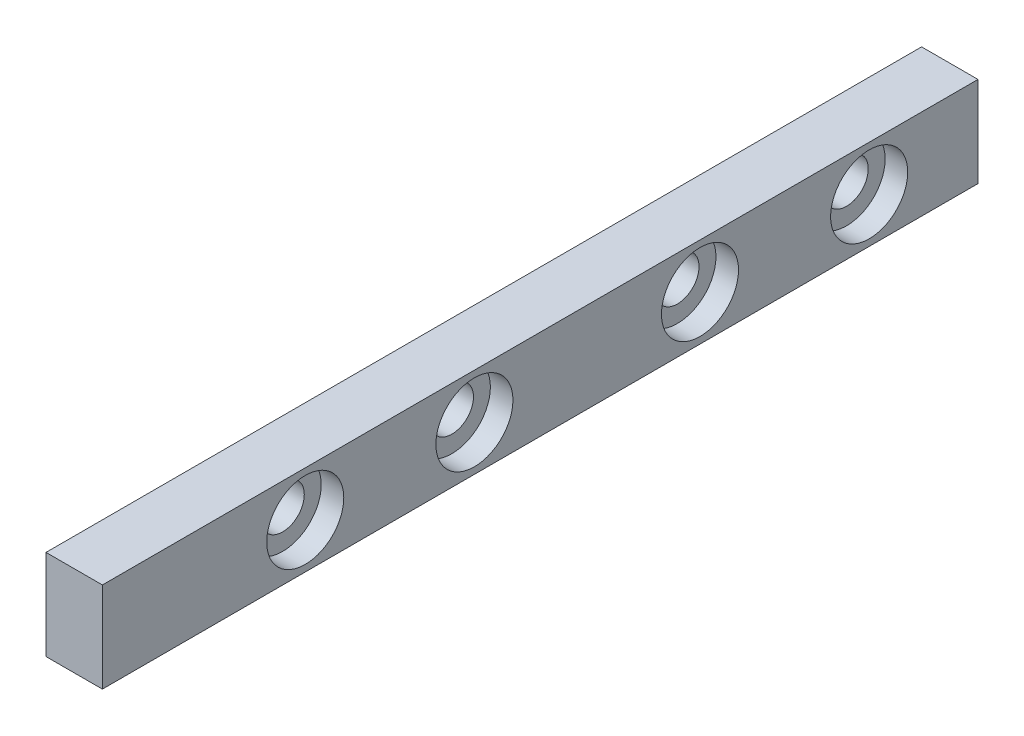
SolidWorks part; units mm, degrees
ref_plane "前视基准面" through (0, 0, 0) normal (0, 0, 1) x (1, 0, 0)
ref_plane "上视基准面" through (0, 0, 0) normal (0, 1, 0) x (1, 0, 0)
ref_plane "右视基准面" through (0, 0, 0) normal (1, 0, 0) x (0, 0, -1)
other "Configuration Table"
sketch "草图1" plane through (0, 0, 0) normal (1, 0, 0) x (0, 0, -1)
  line L0 (0, 2.4) -> (41.58, 2.4) construction
  line L1 (0, 0) -> (41.58, 0)
  line L2 (0, 0) -> (0, 4.8)
  line L3 (0, 4.8) -> (41.58, 4.8)
  line L4 (41.58, 0) -> (41.58, 4.8)
  line L5 (20.79, 4.8) -> (20.79, 0) construction
  circle A0 centre (14.79, 2.4) radius 1.15
  circle A1 centre (5.79, 2.4) radius 1.15
  circle A2 centre (26.79, 2.4) radius 1.15
  circle A3 centre (35.79, 2.4) radius 1.15
  dimension "D3" = 6
  dimension "D5" = 2.3
  dimension "D1" = 4.8
  dimension "D2" = 41.58
  dimension "D4" = 15
extrude "凸台-拉伸1" add sketch "草图1" along normal blind 3
sketch "草图2" plane through (3, 0, 0) normal (1, 0, 0) x (0, 0, -1)
  circle A0 centre (5.79, 2.4) radius 2.05
  circle A1 centre (14.79, 2.4) radius 2.05
  circle A2 centre (26.79, 2.4) radius 2.05
  circle A3 centre (35.79, 2.4) radius 2.05
  dimension "D1" = 4.1
extrude "切除-拉伸1" cut sketch "草图2" against normal blind 1.2
sketch "草图3" plane through (0, 0, 0) normal (0, 0, 1) x (1, 0, 0)
  line L4 (0, 4.8) -> (0, 0)
  line L5 (0, 0) -> (3, 0)
  line L6 (3, 0) -> (3, 4.8)
  line L7 (3, 4.8) -> (0, 4.8)
  line L8 (0, 4.8) -> (0, 0)
  line L9 (0, 0) -> (3, 0)
  line L10 (3, 0) -> (3, 4.8)
  line L11 (3, 4.8) -> (0, 4.8)
  dimension "D1" = 0
extrude "凸台-拉伸2" add sketch "草图3" along normal blind 5
